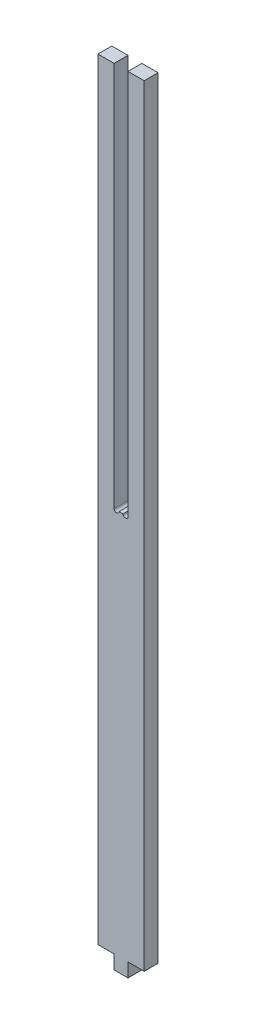
SolidWorks part; units mm, degrees
ref_plane "Piano frontale" through (0, 0, 0) normal (0, 0, 1) x (1, 0, 0)
ref_plane "Piano superiore" through (0, 0, 0) normal (0, 1, 0) x (1, 0, 0)
ref_plane "Piano destro" through (0, 0, 0) normal (1, 0, 0) x (0, 0, -1)
sketch "Schizzo1" plane through (0, 0, 0) normal (0, 0, 1) x (1, 0, 0)
  line L0 (-51.2222, 825) -> (-51.2222, 325)
  line L1 (-72.2222, 825) -> (-51.2222, 825)
  line L2 (-72.2222, 825) -> (-72.2222, -175)
  line L3 (-72.2222, -175) -> (-51.2222, -175)
  line L4 (-12.2222, 825) -> (-12.2222, -175)
  line L5 (-42.2222, 325) -> (-42.2222, -817.501) construction
  line L6 (-33.2222, -175) -> (-12.2222, -175)
  line L7 (-44.8722, 325) -> (-39.5722, 325)
  line L8 (-33.2222, 325) -> (-33.2222, 825)
  line L9 (-33.2222, 825) -> (-12.2222, 825)
  line L11 (-51.2222, -175) -> (-51.2222, -193)
  line L12 (-51.2222, -193) -> (-33.2222, -193)
  line L13 (-33.2222, -175) -> (-33.2222, -193)
  arc A0 (-33.2222, 325) -> (-39.5722, 325) centre (-36.3972, 325) cw
  arc A1 (-51.2222, 325) -> (-44.8722, 325) centre (-48.0472, 325) ccw
  point P0 (-42.766, 325)
  dimension "D5" = 3.175
  dimension "D6" = 3.175
  dimension "D1" = 60
  dimension "D2" = 1000
  dimension "D3" = 18
  dimension "D4" = 21
  dimension "D7" = 18
  dimension "D8" = 18
extrude "Estrusione-Estrusione1" add sketch "Schizzo1" along normal blind 18 contours L4 L6 L13 L12 L11 L3 L2 L1 L0 A1 L7 A0 L8 L9
